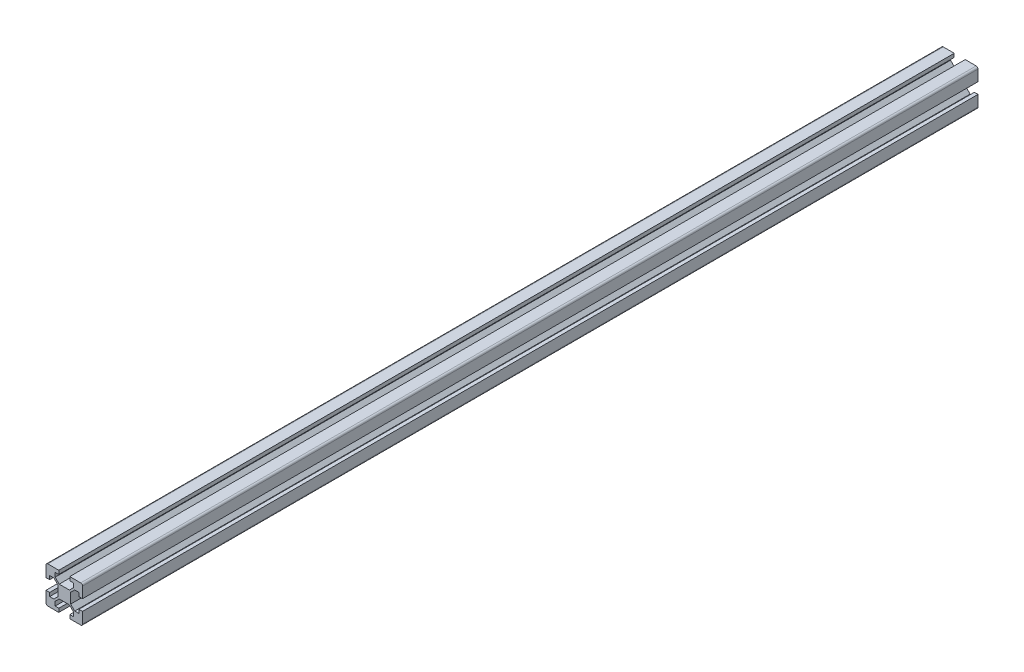
SolidWorks part; units mm, degrees
ref_plane "Front Plane" through (0, 0, 0) normal (0, 0, 1) x (1, 0, 0)
ref_plane "Top Plane" through (0, 0, 0) normal (0, 1, 0) x (1, 0, 0)
ref_plane "Right Plane" through (0, 0, 0) normal (1, 0, 0) x (0, 0, -1)
sketch "Sketch1" plane through (0, 0, 0) normal (0, 0, 1) x (1, 0, 0)
  line L0 (0, 0) -> (10, 10) construction
  line L1 (10, 9) -> (10, 3)
  line L2 (10, 3) -> (8, 3)
  line L3 (8, 3) -> (8, 5)
  line L4 (8, 5) -> (5.7071, 5)
  line L5 (5.7071, 5) -> (3.5, 2.7929)
  line L6 (3.5, 2.7929) -> (3.5, 0)
  line L7 (3.5, 0) -> (0, 0)
  line L8 (0, 3.5) -> (0, 0)
  line L9 (2.7929, 3.5) -> (0, 3.5)
  line L10 (5, 5.7071) -> (2.7929, 3.5)
  line L11 (5, 8) -> (5, 5.7071)
  line L12 (3, 8) -> (5, 8)
  line L13 (3, 10) -> (3, 8)
  line L14 (9, 10) -> (3, 10)
  line L15 (3.5, 0) -> (0, 0)
  line L16 (0, -3.5) -> (0, 0)
  line L17 (2.7929, -3.5) -> (0, -3.5)
  line L18 (5, -5.7071) -> (2.7929, -3.5)
  line L19 (5, -8) -> (5, -5.7071)
  line L20 (3, -8) -> (5, -8)
  line L21 (3, -10) -> (3, -8)
  line L22 (9, -10) -> (3, -10)
  line L23 (10, -9) -> (10, -3)
  line L24 (10, -3) -> (8, -3)
  line L25 (8, -3) -> (8, -5)
  line L26 (8, -5) -> (5.7071, -5)
  line L27 (5.7071, -5) -> (3.5, -2.7929)
  line L28 (3.5, -2.7929) -> (3.5, 0)
  line L29 (0, -3.5) -> (0, 0)
  line L30 (-3.5, 0) -> (0, 0)
  line L31 (-3.5, -2.7929) -> (-3.5, 0)
  line L32 (-5.7071, -5) -> (-3.5, -2.7929)
  line L33 (-8, -5) -> (-5.7071, -5)
  line L34 (-8, -3) -> (-8, -5)
  line L35 (-10, -3) -> (-8, -3)
  line L36 (-10, -9) -> (-10, -3)
  line L37 (-9, -10) -> (-3, -10)
  line L38 (-3, -10) -> (-3, -8)
  line L39 (-3, -8) -> (-5, -8)
  line L40 (-5, -8) -> (-5, -5.7071)
  line L41 (-5, -5.7071) -> (-2.7929, -3.5)
  line L42 (-2.7929, -3.5) -> (0, -3.5)
  line L43 (-3.5, 0) -> (0, 0)
  line L44 (0, 3.5) -> (0, 0)
  line L45 (-2.7929, 3.5) -> (0, 3.5)
  line L46 (-5, 5.7071) -> (-2.7929, 3.5)
  line L47 (-5, 8) -> (-5, 5.7071)
  line L48 (-3, 8) -> (-5, 8)
  line L49 (-3, 10) -> (-3, 8)
  line L50 (-9, 10) -> (-3, 10)
  line L51 (-10, 9) -> (-10, 3)
  line L52 (-10, 3) -> (-8, 3)
  line L53 (-8, 3) -> (-8, 5)
  line L54 (-8, 5) -> (-5.7071, 5)
  line L55 (-5.7071, 5) -> (-3.5, 2.7929)
  line L56 (-3.5, 2.7929) -> (-3.5, 0)
  arc A0 (-10, -9) -> (-9, -10) centre (-9, -9) ccw
  arc A1 (9, -10) -> (10, -9) centre (9, -9) ccw
  arc A2 (9, 10) -> (10, 9) centre (9, 9) cw
  arc A3 (-9, 10) -> (-10, 9) centre (-9, 9) ccw
  point P15 (0, 0)
  point P57 (0, 0)
  dimension "D9" = 1
  dimension "D1" = 45
  dimension "D2" = 7
  dimension "D3" = 2
  dimension "D4" = 2
  dimension "D5" = 0.5
  dimension "D6" = 10
  dimension "D7" = 3.5
  dimension "D8" = 4
extrude "Boss-Extrude1" add sketch "Sketch1" against normal blind 490 contours L50 A3 L51 L52 L53 L54 L55 L56 L30 L8 L45 L46 L47 L48 L49 | L0 L7 L6 L5 L4 L3 L2 L1 A2 | L8 L0 A2 L14 L13 L12 L11 L10 L9 | L36 A0 L37 L38 L39 L40 L41 L42 L16 L30 L31 L32 L33 L34 L35 | L22 A1 L23 L24 L25 L26 L27 L28 L7 L16 L17 L18 L19 L20 L21
